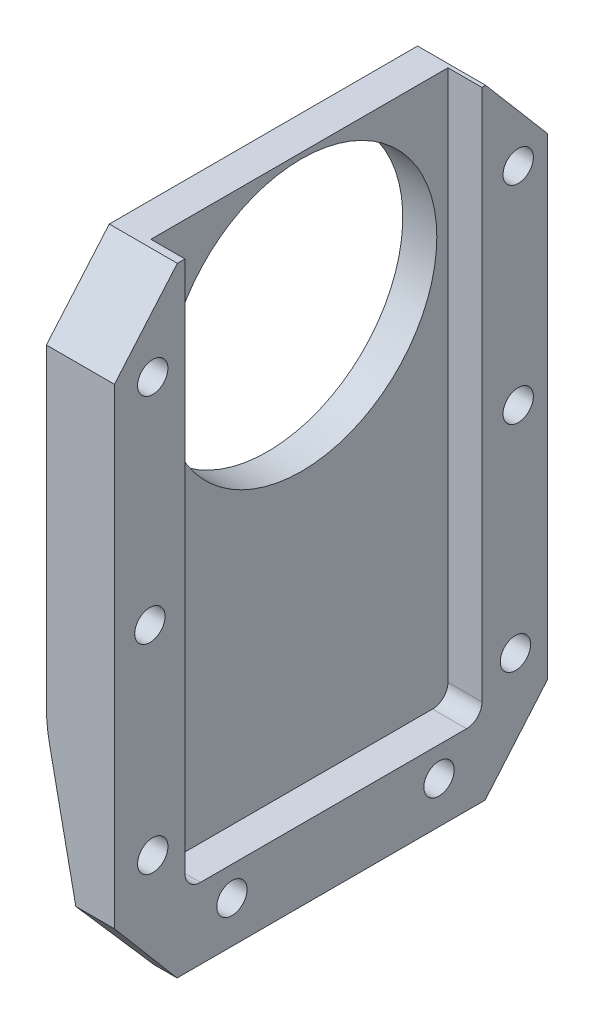
SolidWorks part; units mm, degrees
material "PET"
ref_plane "Front Plane" through (0, 0, 0) normal (0, 0, 1) x (1, 0, 0)
ref_plane "Top Plane" through (0, 0, 0) normal (0, 1, 0) x (1, 0, 0)
ref_plane "Right Plane" through (0, 0, 0) normal (1, 0, 0) x (0, 0, -1)
sketch "Sketch1" plane through (0, 0, 0) normal (0, 0, 1) x (1, 0, 0)
  line L0 (0, 0) -> (0, 50.8)
  line L1 (0, 50.8) -> (-5.588, 50.8)
  line L2 (-5.588, 50.8) -> (-5.588, 17.78)
  line L3 (-5.588, 17.78) -> (-1.9166, 0)
  line L4 (-1.9166, 0) -> (0, 0)
extrude "Boss-Extrude1" add sketch "Sketch1" along normal blind 35.56
fillet "Fillet1" radius 12.7 1 edges at (-5.588, 17.78, 17.78)
hole_wizard "7/8 (0.875) Diameter Hole1" positions "Sketch5" profile "Sketch4" hole size "7/8" standard "ANSI Inch" end condition through all
sketch "Sketch5" plane through (-5.588, 0, 0) normal (-1, 0, 0) x (0, 0, 1)
  point P0 (17.4155, 39.2295)
sketch "Sketch4" plane through (-5.588, 39.2295, 17.4155) normal (0, 1, 0) x (0, 0, 1)
  line L0 (0, 0) -> (0, 5.588)
  line L1 (0, 5.588) -> (11.1125, 5.588)
  line L2 (11.1125, 5.588) -> (11.1125, 0)
  line L5 (11.1125, 0) -> (0, 0)
  line L11 (0, -6.35) -> (0, 107.95) construction
  dimension "Thru Hole Dia." = 22.225
  dimension "Thru Hole Depth" = 5.588
sketch "Sketch6" plane through (0, 0, 0) normal (1, 0, 0) x (0, 0, -1)
  line L0 (-17.78, 50.8) -> (-17.78, 0) construction
  line L1 (-35.56, 50.8) -> (0, 50.8) construction
  line L2 (-35.56, 0) -> (0, 0) construction
  line L4 (-29.772, 50.8) -> (-5.388, 50.8)
  line L5 (-29.772, 50.8) -> (-29.772, 5.842)
  line L6 (-29.772, 5.842) -> (-5.388, 5.842)
  line L7 (-5.388, 50.8) -> (-5.388, 5.842)
  dimension "D1" = 44.958
  dimension "D2" = 24.384
extrude "Cut-Extrude1" cut sketch "Sketch6" against normal blind 2.794
fillet "Fillet2" radius 1.27 2 edges at (-1.397, 5.842, 29.772) (-1.397, 5.842, 5.388)
hole_wizard "#40 (0.098) Diameter Hole1" positions "Sketch9" profile "Sketch8" hole size "#40" standard "ANSI Inch" end condition through all
sketch "Sketch9" plane through (-5.588, 0, 0) normal (-1, 0, 0) x (0, 0, 1)
  point P0 (32.4155, 43.7295)
  point P3 (32.6523, 26.2121)
  point P5 (32.4155, 9.7295)
  point P8 (25.9155, 3.4295)
  point P11 (8.9155, 3.4295)
  point P14 (2.6428, 9.2157)
  point P16 (2.4155, 26.7295)
  point P19 (2.4155, 43.7295)
sketch "Sketch8" plane through (-5.588, 43.7295, 32.4155) normal (0, 1, 0) x (0, 0, 1)
  line L0 (0, 0) -> (0, 5.588)
  line L1 (0, 5.588) -> (1.2446, 5.588)
  line L2 (1.2446, 5.588) -> (1.2446, 0.635)
  line L3 (1.2446, 0.635) -> (1.8796, 0)
  line L5 (1.8796, 0) -> (0, 0)
  line L6 (-1.2446, 0.635) -> (-1.8796, 0) construction
  line L11 (0, -6.35) -> (0, 107.95) construction
  dimension "Thru Hole Dia." = 2.4892
  dimension "Thru Hole Depth" = 5.588
  dimension "Near C'Sink Dia." = 3.7592
  dimension "Near C'Sink Angle" = 90
sketch "Sketch10" plane through (0, 0, 0) normal (1, 0, 0) x (0, 0, -1)
  line L0 (-35.56, 44.7804) -> (-30.3976, 50.8)
  line L1 (-35.56, 0) -> (-35.56, 50.8) construction
  line L2 (-35.56, 50.8) -> (-29.772, 50.8) construction
  line L3 (-30.3976, 50.8) -> (-35.56, 50.8)
  line L4 (-35.56, 50.8) -> (-35.56, 44.7804)
extrude "Cut-Extrude3" cut sketch "Sketch10" against normal through all
sketch "Sketch11" plane through (0, 0, 0) normal (1, 0, 0) x (0, 0, -1)
  line L0 (-5.0855, 50.8) -> (0, 50.8)
  line L1 (-5.388, 50.8) -> (0, 50.8) construction
  line L2 (0, 50.8) -> (0, 44.8249)
  line L3 (0, 0) -> (0, 50.8) construction
  line L4 (0, 44.8249) -> (-5.0855, 50.8)
  line L5 (0, 6.0295) -> (-5.1287, 0)
  line L6 (-35.56, 0) -> (0, 0) construction
  line L7 (-5.1287, 0) -> (0, 0)
  line L8 (0, 0) -> (0, 6.0295)
  line L9 (-35.56, 6.0712) -> (-35.56, 0)
  line L10 (-35.56, 0) -> (-35.56, 44.7804) construction
  line L11 (-35.56, 0) -> (-30.4171, 0)
  line L12 (-30.4171, 0) -> (-35.56, 6.0712)
extrude "Cut-Extrude4" cut sketch "Sketch11" against normal through all
